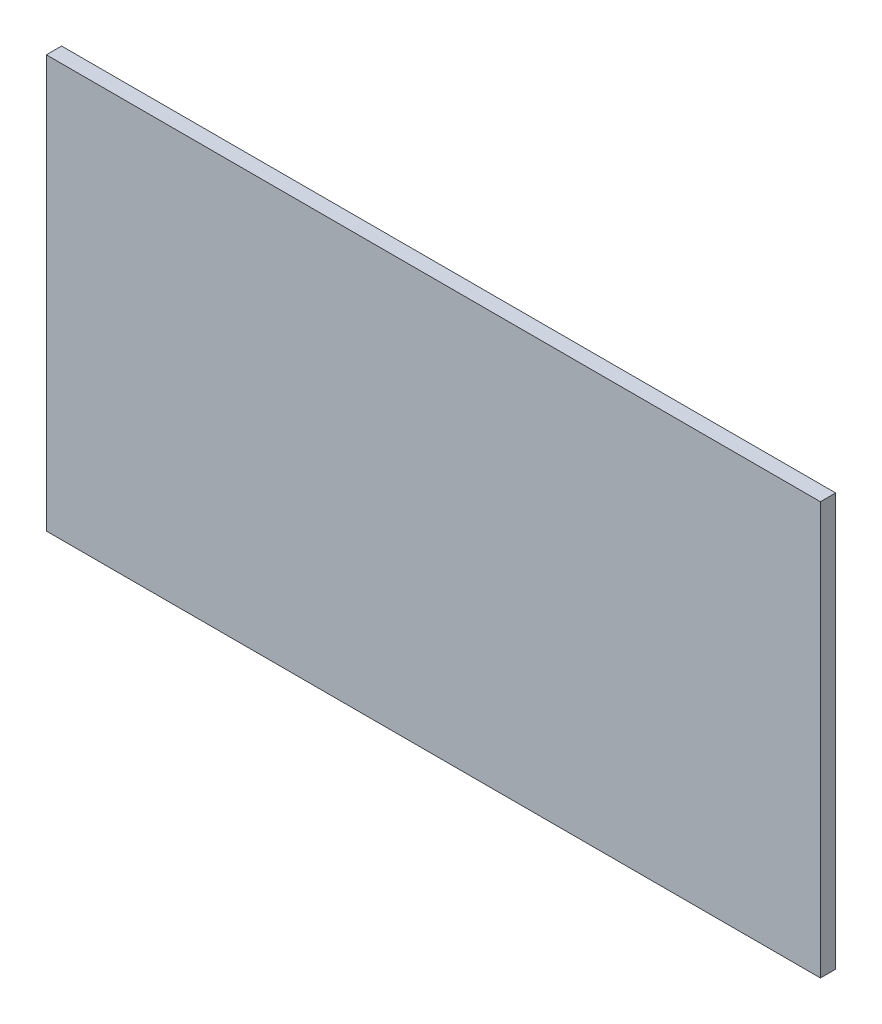
SolidWorks part; units mm, degrees
material "Acrylic (Medium-high impact)"
ref_plane "Front Plane" through (0, 0, 0) normal (0, 0, 1) x (1, 0, 0)
ref_plane "Top Plane" through (0, 0, 0) normal (0, 1, 0) x (1, 0, 0)
ref_plane "Right Plane" through (0, 0, 0) normal (1, 0, 0) x (0, 0, -1)
sketch "Sketch1" plane through (0, 0, 0) normal (0, 0, 1) x (1, 0, 0)
  line L1 (152.4, -81.2) -> (-152.4, -81.2)
  line L2 (152.4, -81.2) -> (152.4, 81.2)
  line L3 (152.4, 81.2) -> (-152.4, 81.2)
  line L4 (-152.4, -81.2) -> (-152.4, 81.2)
  line L5 (152.4, -81.2) -> (-152.4, 81.2) construction
  line L6 (152.4, 81.2) -> (-152.4, -81.2) construction
  point P0 (0, 0)
  dimension "D1" = 162.4
  dimension "D2" = 304.8
extrude "Boss-Extrude1" add sketch "Sketch1" along normal blind 6
